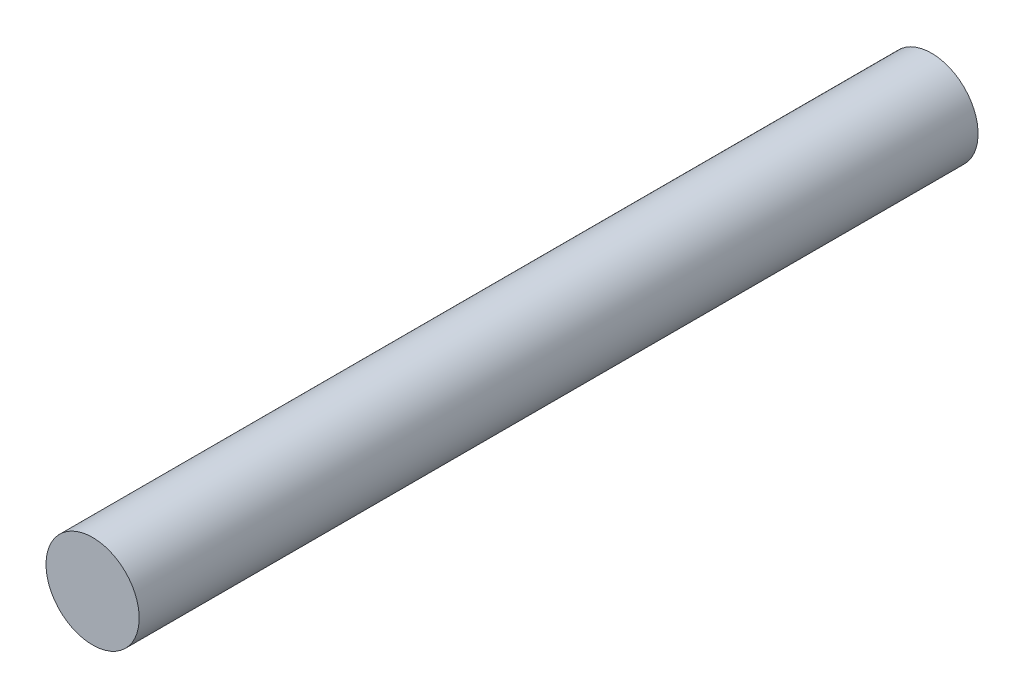
SolidWorks part; units mm, degrees
ref_plane "Front Plane" through (0, 0, 0) normal (0, 0, 1) x (1, 0, 0)
ref_plane "Top Plane" through (0, 0, 0) normal (0, 1, 0) x (1, 0, 0)
ref_plane "Right Plane" through (0, 0, 0) normal (1, 0, 0) x (0, 0, -1)
sketch "Sketch1" plane through (0, 0, 0) normal (0, 0, 1) x (1, 0, 0)
  circle A0 centre (0, 0) radius 12.7
extrude "Boss-Extrude1" add sketch "Sketch1" along normal blind 228.6
